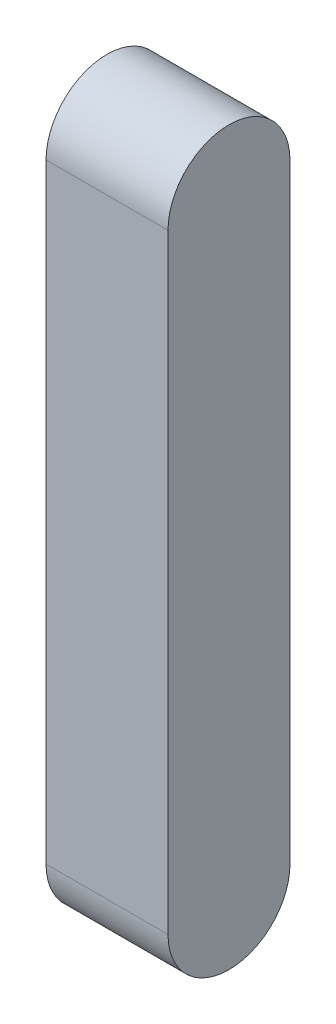
SolidWorks part; units mm, degrees
material "ABS"
ref_plane "前视基准面" through (0, 0, 0) normal (0, 0, 1) x (1, 0, 0)
ref_plane "上视基准面" through (0, 0, 0) normal (0, 1, 0) x (1, 0, 0)
ref_plane "右视基准面" through (0, 0, 0) normal (1, 0, 0) x (0, 0, -1)
sketch "草图1" plane through (0, 0, 0) normal (1, 0, 0) x (0, 0, -1)
  line L1 (-5, 25) -> (5, 25)
  line L2 (-5, 25) -> (-5, -25)
  line L3 (-5, -25) -> (5, -25)
  line L4 (5, 25) -> (5, -25)
  line L5 (-5, 25) -> (5, -25) construction
  line L6 (-5, -25) -> (5, 25) construction
  circle A0 centre (0, 25) radius 5
  circle A1 centre (0, -25) radius 5
  point P0 (0, 0)
extrude "凸台-拉伸1" add sketch "草图1" along normal blind 10 contours L4 L3 L2 L1 | A1 | A0
